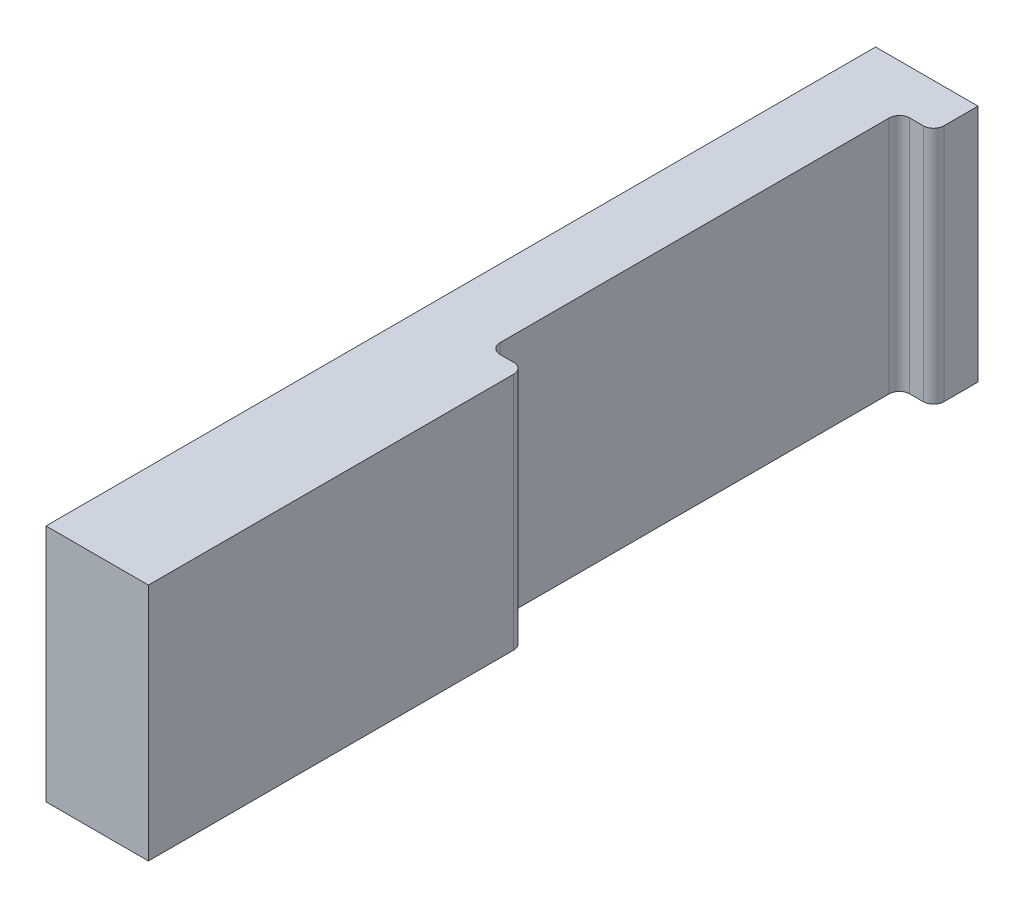
SolidWorks part; units mm, degrees
ref_plane "Front Plane" through (0, 0, 0) normal (0, 0, 1) x (1, 0, 0)
ref_plane "Top Plane" through (0, 0, 0) normal (0, 1, 0) x (1, 0, 0)
ref_plane "Right Plane" through (0, 0, 0) normal (1, 0, 0) x (0, 0, -1)
sketch "Sketch1" plane through (0, 0, 0) normal (0, 1, 0) x (1, 0, 0)
  line L1 (9.7636, 88.501) -> (39.7636, 88.501)
  line L2 (9.7636, 88.501) -> (9.7636, -154.499)
  line L3 (9.7636, -154.499) -> (39.7636, -154.499)
  line L4 (39.7636, 88.501) -> (39.7636, -154.499)
  dimension "D1" = 243
  dimension "D2" = 30
extrude "Boss-Extrude1" add sketch "Sketch1" along normal blind 70
sketch "Sketch2" plane through (0, 70, 0) normal (0, 1, 0) x (1, 0, 0)
  line L0 (39.7636, -154.499) -> (39.7636, 88.501) construction
  line L1 (39.7636, 75.501) -> (29.7636, 75.501)
  line L2 (39.7636, 75.501) -> (39.7636, -44.499)
  line L3 (39.7636, -44.499) -> (29.7636, -44.499)
  line L4 (29.7636, 75.501) -> (29.7636, -44.499)
  line L5 (39.7636, 88.501) -> (9.7636, 88.501) construction
  dimension "D1" = 13
  dimension "D2" = 10
  dimension "D3" = 120
extrude "Cut-Extrude1" cut sketch "Sketch2" against normal blind 70
sketch "Sketch3" plane through (0, 0, 0) normal (0, -1, 0) x (-1, 0, 0)
  line L0 (-9.7636, -154.499) -> (-39.7636, -154.499) construction
  line L1 (-9.7636, 88.501) -> (-9.7636, -154.499) construction
  line L2 (-39.7636, 88.501) -> (-9.7636, 88.501) construction
  line L3 (-29.7636, 75.501) -> (-29.7636, -44.499) construction
  circle A0 centre (-29.7636, -124.499) radius 3
  circle A1 centre (-19.7636, 10.131) radius 3
  dimension "D1" = 30
  dimension "D2" = 20
  dimension "D3" = 78.37
  dimension "D4" = 10
extrude "Cut-Extrude2" cut sketch "Sketch3" against normal blind 20
fillet "Fillet4" radius 3 4 edges at (39.7636, 35, -75.501) (29.7636, 35, -75.501) (39.7636, 35, 44.499) (29.7636, 35, 44.499)
sketch "Sketch4" plane through (0, 70, 0) normal (0, 1, 0) x (1, 0, 0)
  circle A4 centre (29.7636, -124.499) radius 4.9104
extrude "Boss-Extrude2" add sketch "Sketch4" against normal blind 70
sketch "Sketch5" plane through (0, 20, 0) normal (0, -1, 0) x (-1, 0, 0)
  circle A0 centre (-18.4199, 11.102) radius 5.1505
extrude "Boss-Extrude3" add sketch "Sketch5" along normal blind 20
sketch "Sketch6" plane through (0, 0, 0) normal (0, -1, 0) x (-1, 0, 0)
  line L0 (-39.7636, 88.501) -> (-9.7636, 88.501) construction
  line L1 (-29.7636, 72.501) -> (-29.7636, -41.499) construction
  line L2 (-9.7636, -154.499) -> (-39.7636, -154.499) construction
  line L3 (-9.7636, 88.501) -> (-9.7636, -154.499) construction
  circle A0 centre (-19.7636, 10.131) radius 1.5
  circle A1 centre (-29.7636, -124.499) radius 1.5
  dimension "D1" = 78.37
  dimension "D2" = 10
  dimension "D3" = 30
  dimension "D4" = 20
extrude "Cut-Extrude4" cut sketch "Sketch6" against normal blind 20
